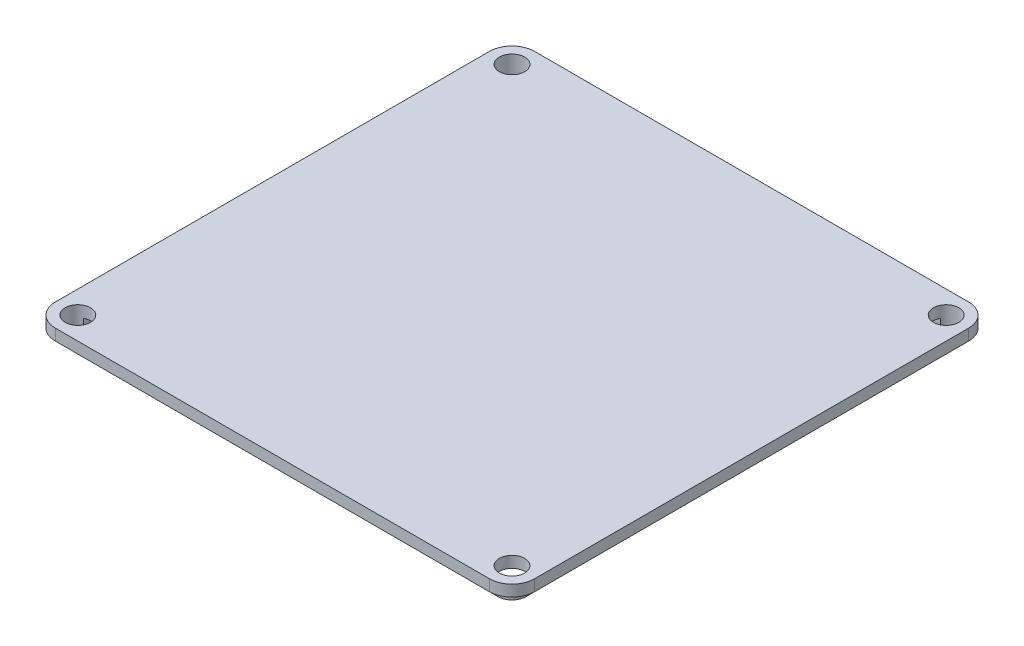
SolidWorks part; units mm, degrees
ref_plane "Front Plane" through (0, 0, 0) normal (0, 0, 1) x (1, 0, 0)
ref_plane "Top Plane" through (0, 0, 0) normal (0, 1, 0) x (1, 0, 0)
ref_plane "Right Plane" through (0, 0, 0) normal (1, 0, 0) x (0, 0, -1)
sketch "Sketch1" plane through (0, 0, 0) normal (0, 1, 0) x (1, 0, 0)
  line L1 (-77, 85) -> (77, 85)
  line L2 (-85, 77) -> (-85, -77)
  line L3 (-77, -85) -> (77, -85)
  line L4 (85, 77) -> (85, -77)
  line L5 (-85, 85) -> (85, -85) construction
  line L6 (-85, -85) -> (85, 85) construction
  arc A0 (-85, -77) -> (-77, -85) centre (-77, -77) ccw
  arc A1 (77, -85) -> (85, -77) centre (77, -77) ccw
  arc A2 (77, 85) -> (85, 77) centre (77, 77) cw
  arc A3 (-77, 85) -> (-85, 77) centre (-77, 77) ccw
  point P0 (0, 0)
  dimension "D3" = 8
  dimension "D1" = 170
  dimension "D2" = 170
extrude "Boss-Extrude1" add sketch "Sketch1" along normal blind 4
sketch "Sketch2" plane through (0, 0, 0) normal (0, -1, 0) x (1, 0, 0)
  line L0 (-82, 77) -> (-82, -77)
  line L1 (-77, -82) -> (77, -82)
  line L2 (82, -77) -> (82, 77)
  line L3 (77, 82) -> (-77, 82)
  line L4 (-85, 77) -> (-85, -77)
  line L5 (-77, -85) -> (77, -85)
  line L6 (85, -77) -> (85, 77)
  line L7 (77, 85) -> (-77, 85)
  line L8 (-85, 77) -> (-85, -77)
  line L9 (-77, -85) -> (77, -85)
  line L10 (85, -77) -> (85, 77)
  line L11 (77, 85) -> (-77, 85)
  line L12 (-79, 77) -> (-79, -77)
  line L13 (-77, -79) -> (77, -79)
  line L14 (79, -77) -> (79, 77)
  line L15 (77, 79) -> (-77, 79)
  arc A0 (-82, -77) -> (-77, -82) centre (-77, -77) ccw
  arc A1 (77, -82) -> (82, -77) centre (77, -77) ccw
  arc A2 (82, 77) -> (77, 82) centre (77, 77) ccw
  arc A3 (-77, 82) -> (-82, 77) centre (-77, 77) ccw
  arc A4 (-77, 85) -> (-85, 77) centre (-77, 77) ccw
  arc A5 (-85, -77) -> (-77, -85) centre (-77, -77) ccw
  arc A6 (77, -85) -> (85, -77) centre (77, -77) ccw
  arc A7 (85, 77) -> (77, 85) centre (77, 77) ccw
  arc A8 (-77, 85) -> (-85, 77) centre (-77, 77) ccw
  arc A9 (-85, -77) -> (-77, -85) centre (-77, -77) ccw
  arc A10 (77, -85) -> (85, -77) centre (77, -77) ccw
  arc A11 (85, 77) -> (77, 85) centre (77, 77) ccw
  arc A12 (-77, 79) -> (-79, 77) centre (-77, 77) ccw
  arc A13 (-79, -77) -> (-77, -79) centre (-77, -77) ccw
  arc A14 (77, -79) -> (79, -77) centre (77, -77) ccw
  arc A15 (79, 77) -> (77, 79) centre (77, 77) ccw
  dimension "D1" = 0
  dimension "D2" = 3
  dimension "D3" = 3
extrude "Boss-Extrude2" add sketch "Sketch2" along normal blind 3 contours L3 A3 L0 A0 L1 A1 L2 A2 A15 L14 A14 L13 A13 L12 A12 L15
sketch "Sketch4" plane through (0, -3, 0) normal (0, -1, 0) x (1, 0, 0)
  circle A0 centre (77, 77) radius 4.5
  circle A1 centre (77, -77) radius 4.5
  circle A2 centre (-77, -77) radius 4.5
  circle A3 centre (-77, 77) radius 4.5
  dimension "D1" = 9
extrude "Cut-Extrude2" cut sketch "Sketch4" against normal through all
equation "\"A\"= 170"
equation "\"B\"= 40"
equation "\"D1@Sketch1\"=\"A\""
equation "\"D2@Sketch1\"=\"A\""
equation "\"C\"= 8"
